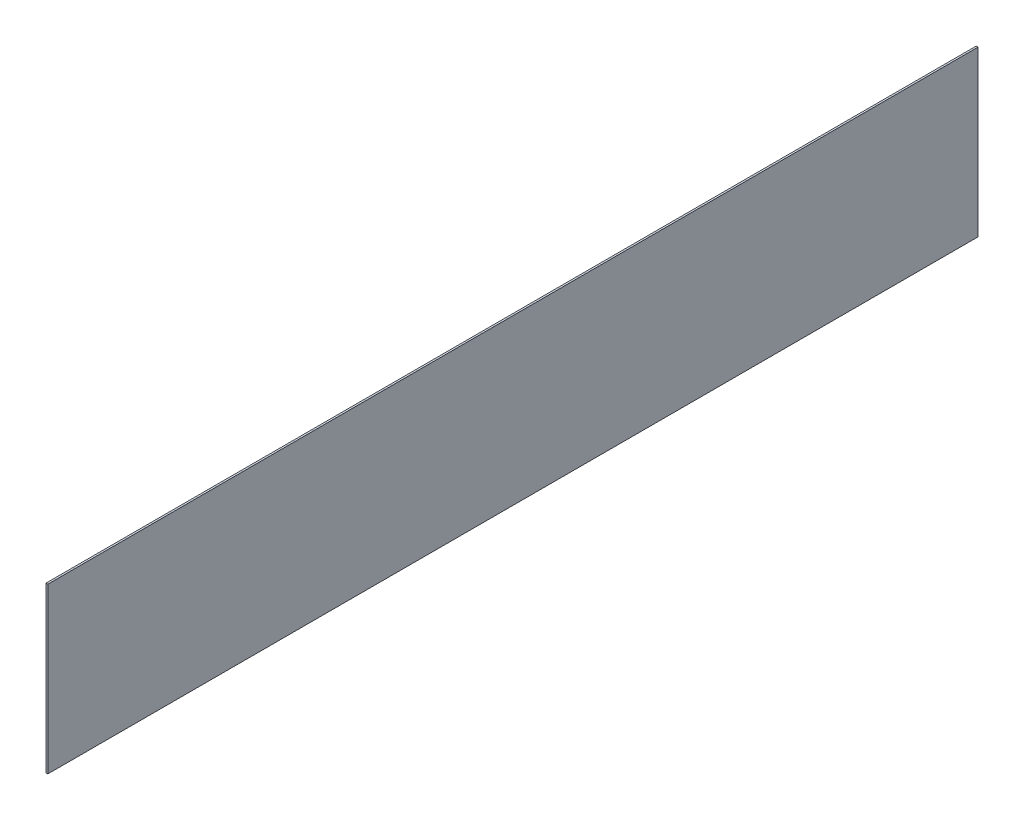
SolidWorks part; units mm, degrees
material "1023 碳钢板 (SS)"
ref_plane "前视基准面" through (0, 0, 0) normal (0, 0, 1) x (1, 0, 0)
ref_plane "上视基准面" through (0, 0, 0) normal (0, 1, 0) x (1, 0, 0)
ref_plane "右视基准面" through (0, 0, 0) normal (1, 0, 0) x (0, 0, -1)
sketch "草图1" plane through (0, 0, 0) normal (0, 0, 1) x (1, 0, 0)
  line L1 (-6, 530) -> (6, 530)
  line L2 (-6, 530) -> (-6, -530)
  line L3 (-6, -530) -> (6, -530)
  line L4 (6, 530) -> (6, -530)
  line L5 (-6, 530) -> (6, -530) construction
  line L6 (-6, -530) -> (6, 530) construction
  point P0 (0, 0)
  dimension "D1" = 12
  dimension "D2" = 1060
extrude "凸台-拉伸1" add sketch "草图1" along normal mid plane 6000
equation "\"零件重量\"= \"SW-质量\""
